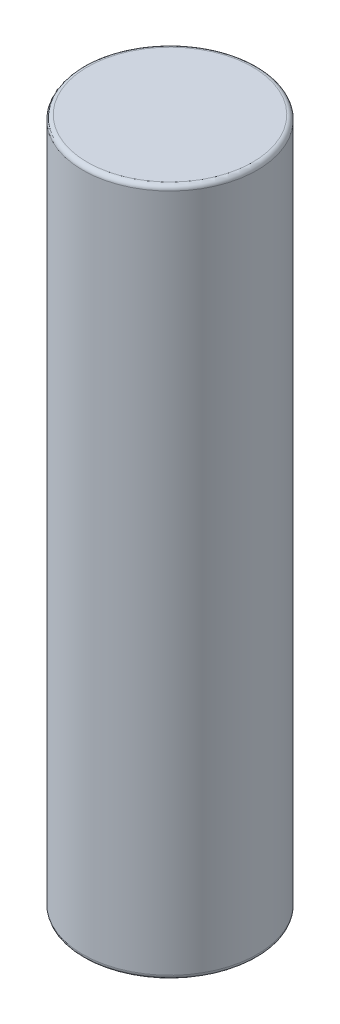
SolidWorks part; units mm, degrees
ref_plane "Front Plane" through (0, 0, 0) normal (0, 0, 1) x (1, 0, 0)
ref_plane "Top Plane" through (0, 0, 0) normal (0, 1, 0) x (1, 0, 0)
ref_plane "Right Plane" through (0, 0, 0) normal (1, 0, 0) x (0, 0, -1)
sketch "Sketch1" plane through (0, 0, 0) normal (0, 1, 0) x (1, 0, 0)
  circle A0 centre (0, 0) radius 4.826
  dimension "D1" = 9.652
extrude "Boss-Extrude1" add sketch "Sketch1" along normal mid plane 38.1
fillet "Fillet1" radius 0.254 2 edges at (0, -19.05, 4.826) (0, 19.05, 4.826)
